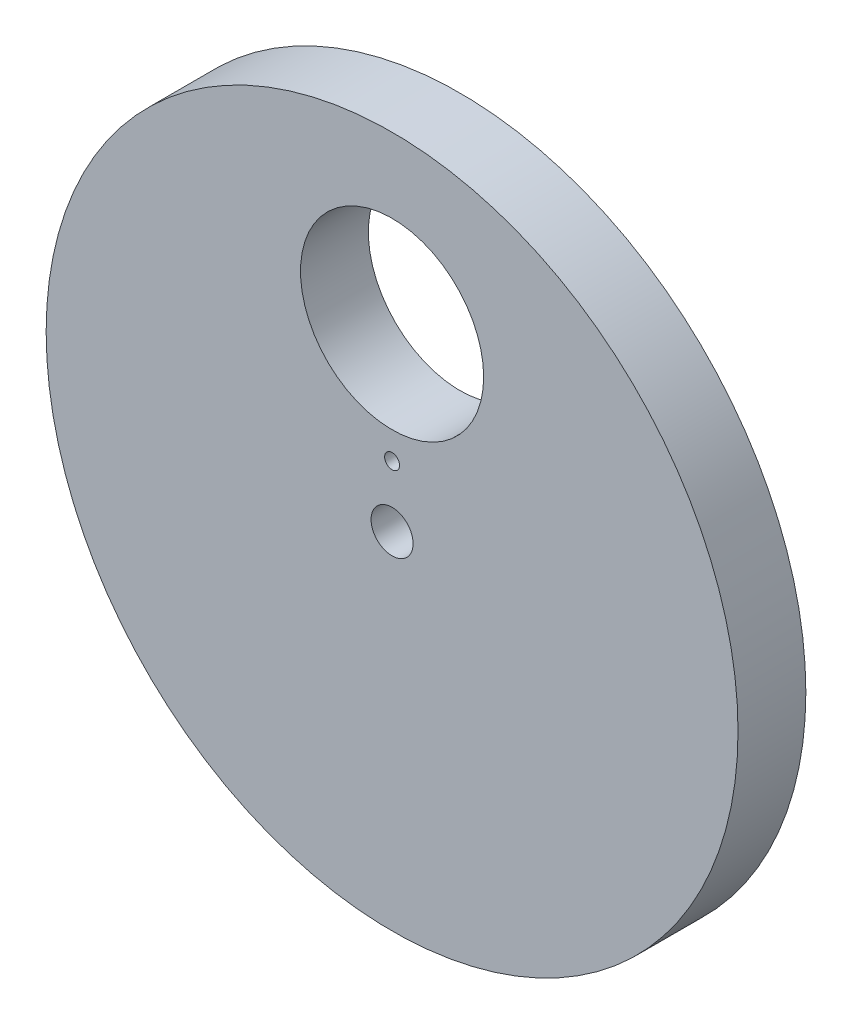
SolidWorks part; units mm, degrees
ref_plane "Ebene vorne" through (0, 0, 0) normal (0, 0, 1) x (1, 0, 0)
ref_plane "Ebene oben" through (0, 0, 0) normal (0, 1, 0) x (1, 0, 0)
ref_plane "Ebene rechts" through (0, 0, 0) normal (1, 0, 0) x (0, 0, -1)
sketch "Skizze1" plane through (0, 0, 0) normal (0, 0, 1) x (1, 0, 0)
  circle A0 centre (0, 0) radius 25.5
  dimension "D1" = 51
extrude "Aufsatz-Linear austragen1" add sketch "Skizze1" along normal blind 5
sketch "Skizze2" plane through (0, 0, 5) normal (0, 0, 1) x (1, 0, 0)
  circle A0 centre (0, 0) radius 1.55
  circle A1 centre (0, 4.5) radius 0.55
  circle A2 centre (0, 13.25) radius 6.75
  dimension "D1" = 3.1
  dimension "D2" = 1.1
  dimension "D4" = 13.5
  dimension "D3" = 4.5
  dimension "D5" = 13.25
extrude "Schnitt-Linear austragen1" cut sketch "Skizze2" against normal through all both and the other way through all
